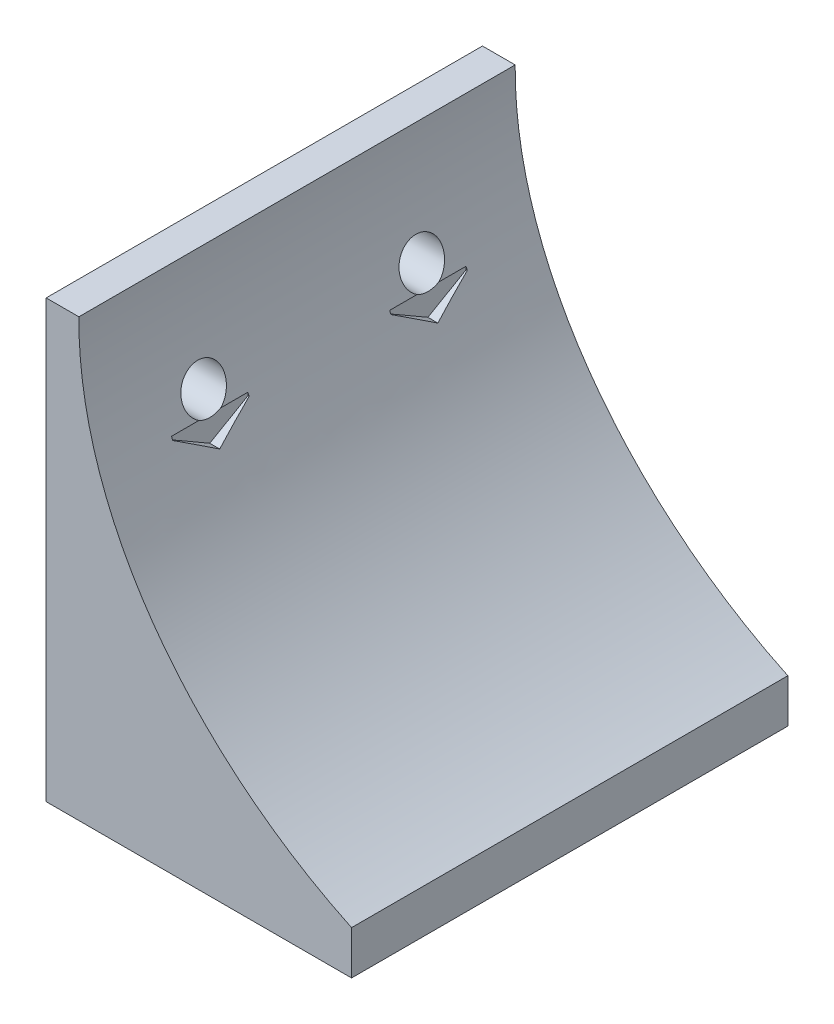
SolidWorks part; units mm, degrees
ref_plane "前视基准面" through (0, 0, 0) normal (0, 0, 1) x (1, 0, 0)
ref_plane "上视基准面" through (0, 0, 0) normal (0, 1, 0) x (1, 0, 0)
ref_plane "右视基准面" through (0, 0, 0) normal (1, 0, 0) x (0, 0, -1)
sketch "草图1" plane through (0, 0, 0) normal (0, 0, 1) x (1, 0, 0)
  line L0 (0, 40) -> (0, 0)
  line L1 (0, 0) -> (28, 0)
  line L3 (28, 0) -> (28, 40) construction
  line L4 (28, 40) -> (0, 40) construction
  line L5 (28, 0) -> (28, 4)
  line L6 (0, 40) -> (3, 40)
  spline S0 degree 3 poles (28, 4) (14.2704, 10.4911) (2.8873, 23.8367) (3, 40) knots 0 0 0 0 1 1 1 1
  dimension "D3" = 3
  dimension "D1" = 28
  dimension "D2" = 40
  dimension "D5" = 4
extrude "凸台-拉伸1" add sketch "草图1" along normal mid plane 40
sketch "草图2" plane through (0, 0, 0) normal (1, 0, 0) x (0, 0, -1)
  line L0 (-20, 30) -> (20, 30) construction
  line L1 (-20, 40) -> (-20, 4) construction
  line L2 (20, 4) -> (20, 40) construction
  line L3 (-20, 40) -> (20, 40) construction
  line L4 (0, 40) -> (0, 0) construction
  circle A0 centre (-10, 30) radius 2
  circle A1 centre (10, 30) radius 2
  dimension "D2" = 4
  dimension "D3" = 20
  dimension "D1" = 10
extrude "切除-拉伸2" cut sketch "草图2" against normal mid plane 20
ref_plane "基准面1" through (5, 0, 0) normal (1, 0, 0) x (0, 0, -1)
sketch "草图3" plane through (5, 0, 0) normal (1, 0, 0) x (0, 0, -1)
  line L1 (-10, 34.0415) -> (-13.5, 32.0207)
  line L2 (-13.5, 32.0207) -> (-13.5, 27.9793)
  line L3 (-13.5, 27.9793) -> (-10, 25.9585)
  line L4 (-10, 25.9585) -> (-6.5, 27.9793)
  line L5 (-6.5, 27.9793) -> (-6.5, 32.0207)
  line L6 (-6.5, 32.0207) -> (-10, 34.0415)
  line L7 (10, 34.0415) -> (6.5, 32.0207)
  line L8 (6.5, 32.0207) -> (6.5, 27.9793)
  line L9 (6.5, 27.9793) -> (10, 25.9585)
  line L10 (10, 25.9585) -> (13.5, 27.9793)
  line L11 (13.5, 27.9793) -> (13.5, 32.0207)
  line L12 (13.5, 32.0207) -> (10, 34.0415)
  circle A0 centre (-10, 30) radius 3.5 construction
  circle A1 centre (10, 30) radius 3.5 construction
  dimension "D1" = 7
extrude "切除-拉伸3" cut sketch "草图3" along normal blind 20
equation "\"41、\"=46"
